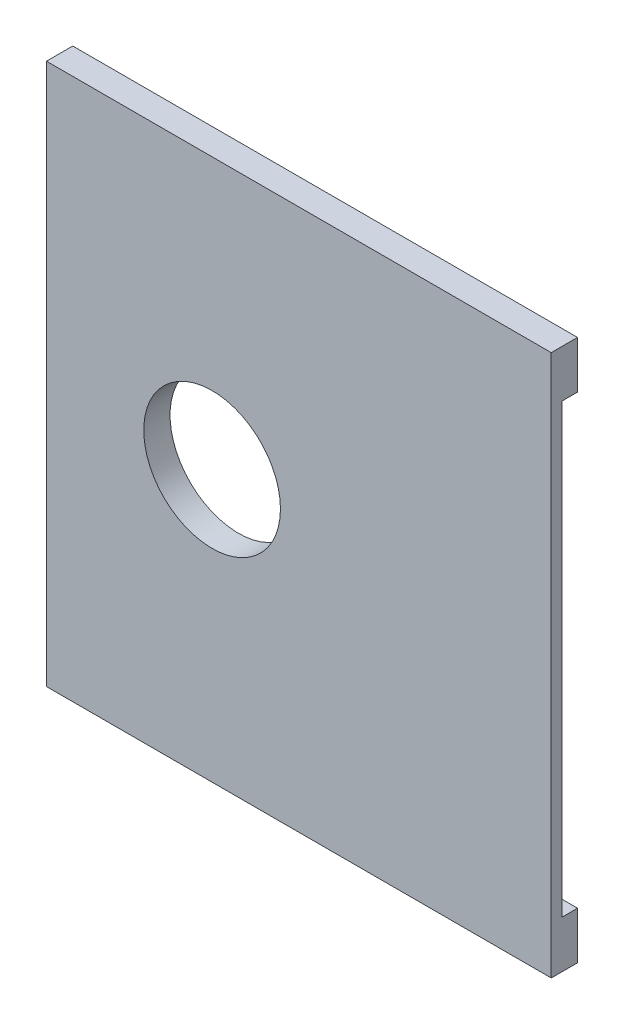
SolidWorks part; units mm, degrees
material "Nylon 6/10"
ref_plane "Front Plane" through (0, 0, 0) normal (0, 0, 1) x (1, 0, 0)
ref_plane "Top Plane" through (0, 0, 0) normal (0, 1, 0) x (1, 0, 0)
ref_plane "Right Plane" through (0, 0, 0) normal (1, 0, 0) x (0, 0, -1)
sketch "Sketch2" plane through (0, 0, 0) normal (0, 0, 1) x (1, 0, 0)
  line L0 (5.3, 8.5) -> (5.3, -8.5) construction
  line L1 (5.3, 8.5) -> (5.3, -8.5) construction
  line L2 (-6.3, 10.3) -> (-6.3, -10.3) construction
  line L3 (-6.3, 10.3) -> (-6.3, -10.3)
  line L4 (6.3, -8.5) -> (6.3, 8.5) construction
  line L5 (-5.3, 8.5) -> (6.3, 8.5) construction
  line L6 (-5.3, 8.5) -> (-5.3, -8.5) construction
  line L7 (-5.3, -8.5) -> (6.3, -8.5) construction
  line L9 (-6.3, 10.3) -> (-5.3, 10.3)
  line L10 (-5.3, 8.5) -> (-5.3, 10.3) construction
  line L11 (6.3, -8.5) -> (6.3, 8.5) construction
  line L12 (8.1, -10.3) -> (8.1, 10.3) construction
  line L13 (8.1, -10.3) -> (8.1, 10.3) construction
  line L14 (-5.3, 10.3) -> (6.3, 10.3)
  line L15 (6.3, 8.5) -> (6.3, 10.3) construction
  line L16 (-6.3, -10.3) -> (-5.3, -10.3)
  line L17 (-5.3, -8.5) -> (-5.3, -10.3) construction
  line L18 (-5.3, -10.3) -> (6.3, -10.3)
  line L19 (6.3, -10.3) -> (6.3, -8.5) construction
  line L20 (6.3, -10.3) -> (8.1, -10.3)
  line L21 (6.3, 10.3) -> (8.1, 10.3)
  line L22 (-8.6, 13.1) -> (10.4, 13.1) construction
  line L23 (-8.6, 13.1) -> (10.4, 13.1) construction
  line L24 (10.9, 12.6) -> (10.9, -12.6) construction
  line L25 (10.9, 12.6) -> (10.9, -12.6) construction
  line L26 (-9.1, -12.6) -> (-9.1, 12.6) construction
  line L27 (-9.1, -12.6) -> (-9.1, 12.6) construction
  line L30 (10.4, -13.1) -> (-8.6, -13.1) construction
  line L31 (10.4, -13.1) -> (-8.6, -13.1) construction
  line L33 (12.9, -10.3) -> (12.9, 10.3)
  line L37 (0, 0) -> (-2.6, 0) construction
  line L39 (8.1, 10.3) -> (12.9, 10.3)
  line L40 (8.1, -10.3) -> (12.9, -10.3)
  line L41 (11.9, -10.3) -> (11.9, 10.3) construction
  circle A0 centre (0, 0) radius 17.2417 construction
  circle A2 centre (0, 0) radius 2.6
  circle A3 centre (0, 0) radius 17.2417 construction
  dimension "D1" = 5.2
  dimension "D2" = 1
  dimension "D3" = 1
  dimension "D5" = 2
extrude "Boss-Extrude1" add sketch "Sketch2" along normal blind 1
ref_plane "Plane1" through (0, 0, 1) normal (0, 0, 1) x (1, 0, 0)
sketch "Sketch3" plane through (0, 0, 0) normal (0, 0, 1) x (1, 0, 0)
  line L0 (5.3, 8.5) -> (5.3, -8.5) construction
  line L1 (5.3, 8.5) -> (5.3, -8.5)
  line L2 (6.3, -8.5) -> (6.3, 8.5) construction
  line L3 (6.3, -8.5) -> (6.3, 8.5) construction
  line L4 (-5.3, 8.5) -> (6.3, 8.5) construction
  line L5 (5.3, 8.5) -> (6.3, 8.5)
  line L6 (-5.3, -8.5) -> (6.3, -8.5) construction
  line L7 (5.3, -8.5) -> (6.3, -8.5)
  line L8 (6.3, 8.5) -> (12.9, 8.5)
  line L9 (12.9, -10.3) -> (12.9, 10.3) construction
  line L10 (12.9, 8.5) -> (12.9, -8.5)
  line L11 (12.9, -8.5) -> (6.3, -8.5)
extrude "Cut-Extrude1" cut sketch "Sketch3" along normal blind 0.6
